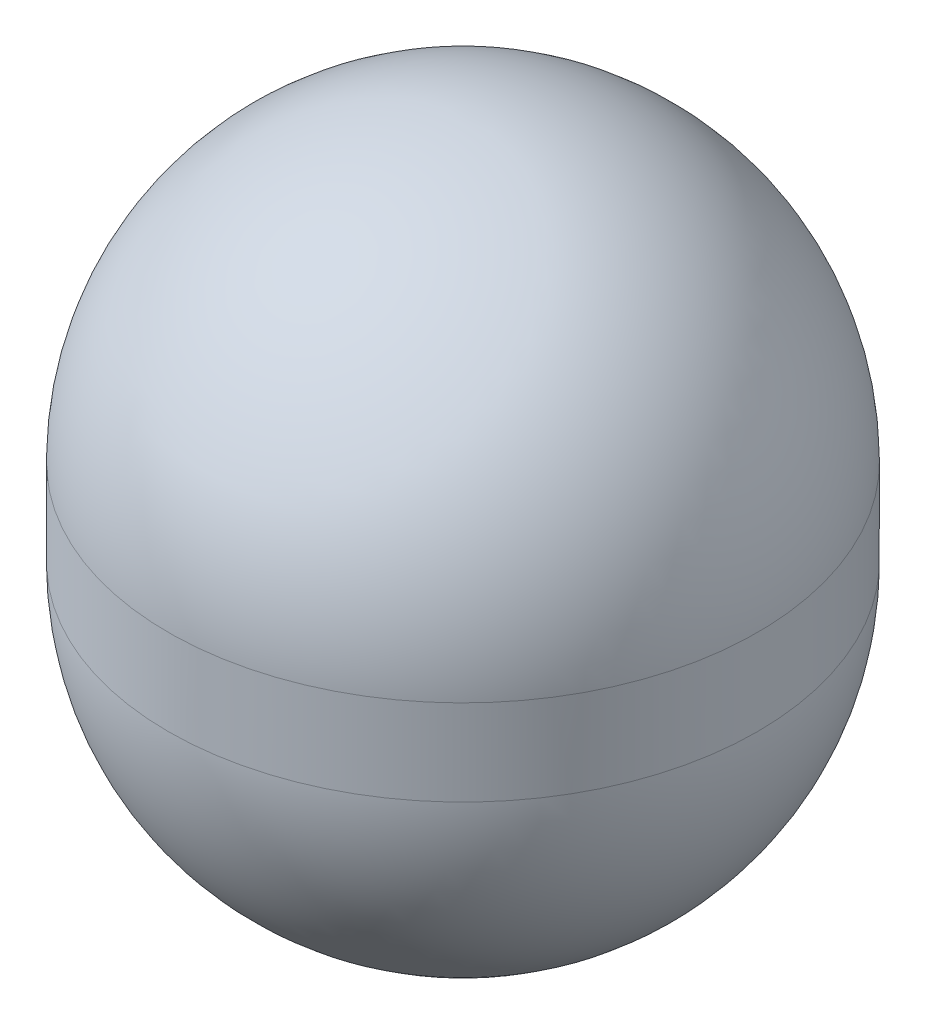
SolidWorks part; units mm, degrees
other "Blob"
ref_plane "Front Plane" through (0, 0, 0) normal (0, 0, 1) x (1, 0, 0)
ref_plane "Top Plane" through (0, 0, 0) normal (0, 1, 0) x (1, 0, 0)
ref_plane "Right Plane" through (0, 0, 0) normal (1, 0, 0) x (0, 0, -1)
sketch "Revolve Profile" plane through (0, 0, 0) normal (0, 0, 1) x (1, 0, 0)
  line L0 (0, -0.275) -> (0, 0.275)
  line L1 (-0.24, 0.035) -> (-0.24, -0.035)
  line L2 (0, 0) -> (0, 0.55) construction
  arc A0 (0, 0.275) -> (-0.24, 0.035) centre (0, 0.035) ccw
  arc A1 (-0.24, -0.035) -> (0, -0.275) centre (0, -0.035) ccw
  dimension "fillet radius" = 0.24
  dimension "height" = 0.55
  dimension "diameter" = 0.48
revolve "Revolve1" add sketch "Revolve Profile" angle 180 about L2
sketch "Extrude Profile" plane through (0, 0, 0) normal (0, 0, 1) x (1, 0, 0)
  line L2 (-0.24, 0.035) -> (-0.24, -0.035)
  line L3 (0.24, -0.035) -> (0.24, 0.035)
  line L4 (-0.24, 0.035) -> (-0.24, -0.035)
  line L5 (0.24, -0.035) -> (0.24, 0.035)
  arc A2 (0.24, 0.035) -> (-0.24, 0.035) centre (0, 0.035) ccw
  arc A3 (-0.24, -0.035) -> (0.24, -0.035) centre (0, -0.035) ccw
  arc A4 (0.24, 0.035) -> (-0.24, 0.035) centre (0, 0.035) ccw
  arc A5 (-0.24, -0.035) -> (0.24, -0.035) centre (0, -0.035) ccw
  point P0 (0, 0)
  dimension "D1" = 0
mirror "Mirror1" about plane through (0, 0, 0) normal (0, 0, 1) of bodies 101
